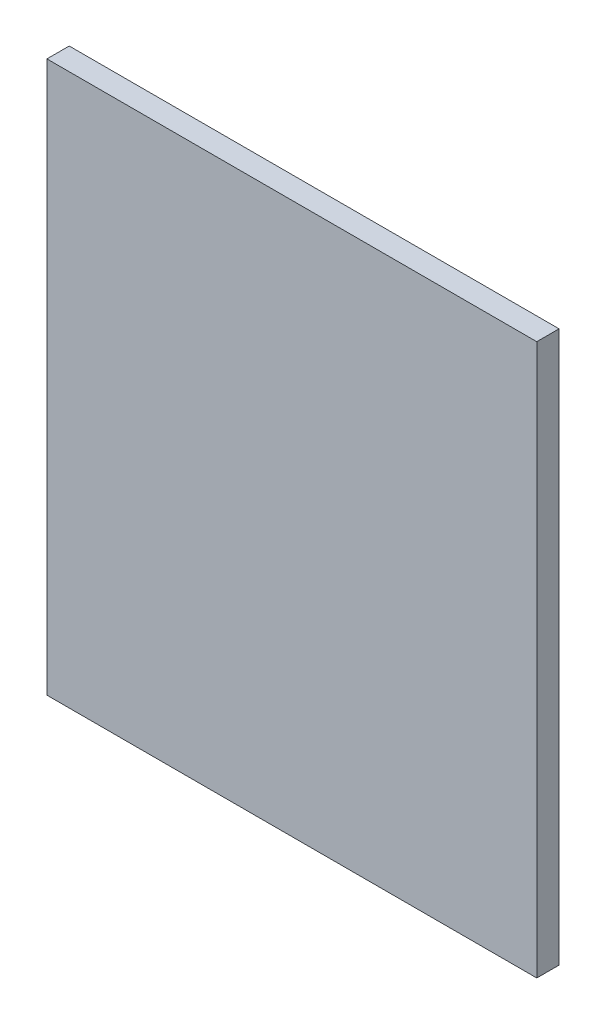
SolidWorks part; units mm, degrees
ref_plane "前视基准面" through (0, 0, 0) normal (0, 0, 1) x (1, 0, 0)
ref_plane "上视基准面" through (0, 0, 0) normal (0, 1, 0) x (1, 0, 0)
ref_plane "右视基准面" through (0, 0, 0) normal (1, 0, 0) x (0, 0, -1)
sketch "草图1" plane through (0, 0, 0) normal (0, 0, 1) x (1, 0, 0)
  line L1 (-15.1392, 11.7823) -> (16.0608, 11.7823)
  line L2 (-15.1392, 11.7823) -> (-15.1392, -23.3177)
  line L3 (-15.1392, -23.3177) -> (16.0608, -23.3177)
  line L4 (16.0608, 11.7823) -> (16.0608, -23.3177)
  dimension "D1" = 31.2
  dimension "D2" = 35.1
extrude "凸台-拉伸1" add sketch "草图1" along normal blind 1.42 contours L1 L4 L3 L2
